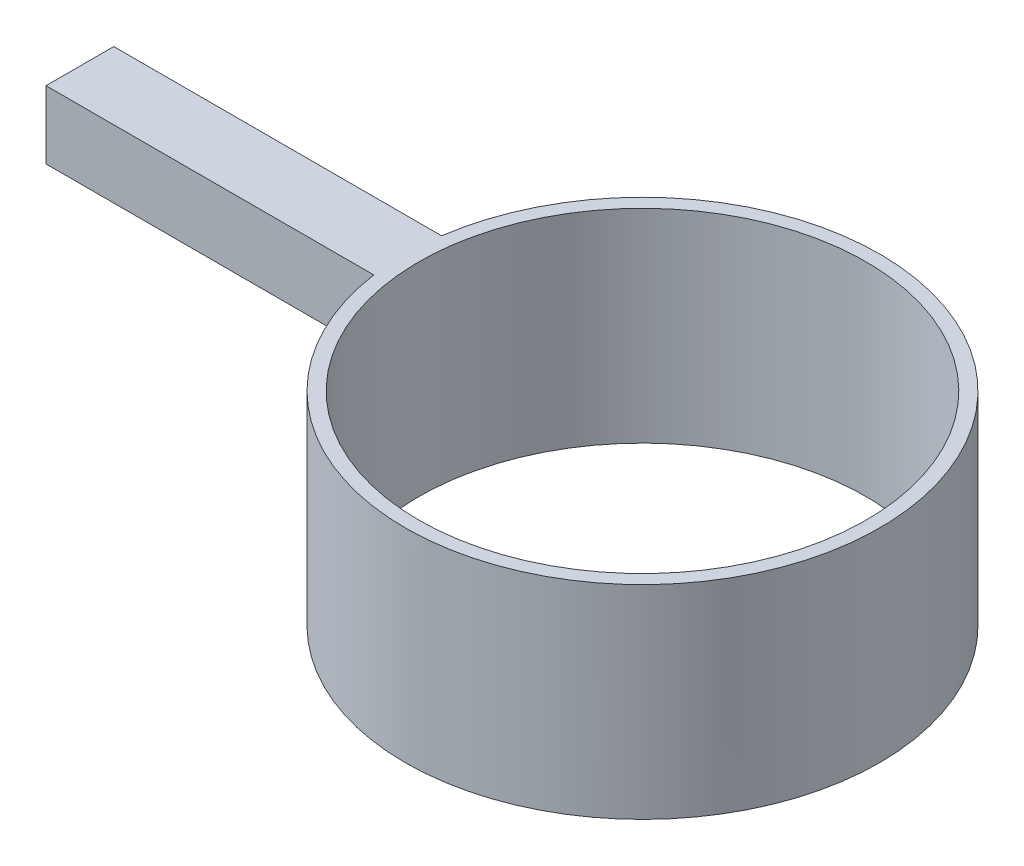
SolidWorks part; units mm, degrees
ref_plane "Front Plane" through (0, 0, 0) normal (0, 0, 1) x (1, 0, 0)
ref_plane "Top Plane" through (0, 0, 0) normal (0, 1, 0) x (1, 0, 0)
ref_plane "Right Plane" through (0, 0, 0) normal (1, 0, 0) x (0, 0, -1)
sketch "Sketch1" plane through (0, 0, 0) normal (0, 1, 0) x (1, 0, 0)
  circle A0 centre (0, 0) radius 33
  circle A1 centre (0, 0) radius 35
  dimension "D1" = 66
  dimension "D2" = 2
extrude "Boss-Extrude1" add sketch "Sketch1" along normal blind 30
sketch "Sketch2" plane through (0, 30, 0) normal (0, 1, 0) x (1, 0, 0)
  line L1 (-33, 5) -> (-83, 5)
  line L2 (-33, 5) -> (-33, -5)
  line L3 (-33, -5) -> (-83, -5)
  line L4 (-83, 5) -> (-83, -5)
  circle A1 centre (0, 0) radius 33 construction
  point P4 (-33, 0)
  dimension "D1" = 10
  dimension "D2" = 33
  dimension "D3" = 50
extrude "Boss-Extrude2" add sketch "Sketch2" against normal blind 10
